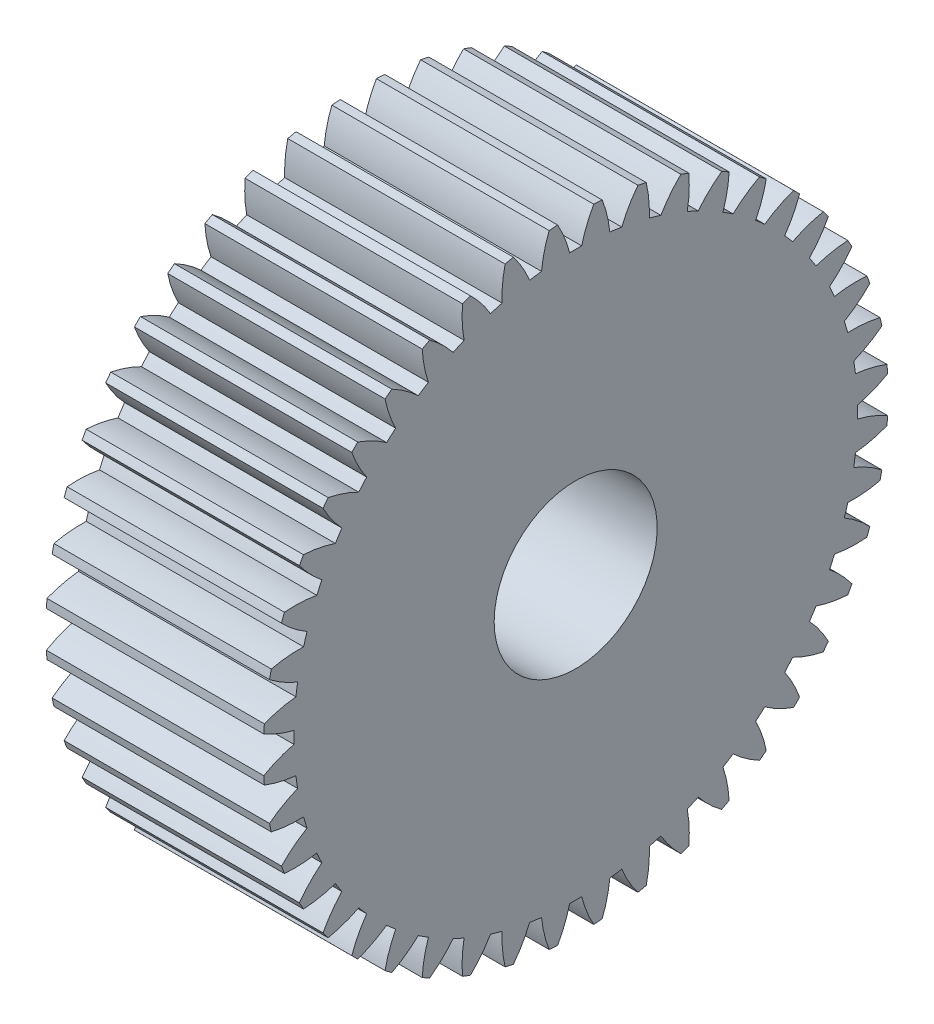
SolidWorks part; units mm, degrees
ref_plane "Plane1" through (0, 0, 0) normal (0, 0, 1) x (1, 0, 0)
ref_plane "Plane2" through (0, 0, 0) normal (0, 1, 0) x (1, 0, 0)
ref_plane "Plane3" through (0, 0, 0) normal (1, 0, 0) x (0, 0, -1)
sketch "HoldingSke" plane through (0, 0, 0) normal (0, 1, 0) x (1, 0, 0)
  line L0 (0, 0) -> (1.4387, -1.3893)
  line L1 (-15, 0) -> (100, 0) construction
  line L2 (0, 0) -> (-2.1039, 2.3779)
  line L3 (0, 0) -> (-11.863, 4.5341)
  line L4 (0, 0) -> (6.2122, 5.9991)
  line L5 (0, 0) -> (-46.8476, -17.4728)
  line L6 (0, 0) -> (-6.6317, -4.4744)
  line L7 (-2.1039, 2.3779) -> (8.6586, 51.2059)
  line L8 (-76.2, 54.61) -> (-75.2, 54.61)
  line L9 (-71.009, 38.7566) -> (-53.1078, 45.2721)
  line L10 (-76.2, 71.12) -> (104.1128, 71.12)
  line L11 (0, 0) -> (-8, 0)
  line L12 (-76.2, 101.6) -> (-76.181, 101.6)
  line L13 (24.9733, 27.94) -> (52.9518, 28.4284)
  line L14 (24.9733, 27.94) -> (24.9743, 27.94)
  line L15 (24.9733, 27.94) -> (100.4006, 29.5858)
  line L16 (-63.627, -0.5) -> (-12.827, -0.5)
  circle A0 centre (0, 0) radius 3
  circle A1 centre (0, 0) radius 10.374
  circle A2 centre (0, 0) radius 37.5
  circle A3 centre (0, 0) radius 3
  dimension "MHD" = 20.748
  dimension "Hub_dia" = 75
  dimension "Bore" = 6
  dimension "MBD" = 6
  dimension "Num_teeth" = 44
  dimension "Pitch" = 2
  dimension "Overall_len" = 50
  dimension "Show_teeth" = 44
  dimension "Thickness" = 8
  dimension "OAL" = 50.0001
  dimension "T_dim" = 1
  dimension "Ap" = 20
  dimension "H" = 19.05
  dimension "Pitch_radius" = 180.3128
  dimension "Width" = 8
  dimension "Backlash" = 0.019
  dimension "Addendum_fac" = 1
  dimension "Dedendum_fac" = 1.25
  dimension "Clearance_fac" = 0.25
  dimension "Dedendum_add" = 0.001
  dimension "Module" = 0.5
sketch "BasProSke" plane through (0, 0, 0) normal (0, 1, 0) x (1, 0, 0)
  line L0 (-10, 0) -> (60, 0) construction
  line L1 (0, 0) -> (0, 11.5)
  line L2 (0, 0) -> (8, 0)
  line L3 (8, 0) -> (8, 11.5)
  line L4 (8, 11.5) -> (0, 11.5)
  dimension "Thickness" = 8
  dimension "Diameter" = 23
revolve "Base-Revolve" add sketch "BasProSke" angle 360 about L0
sketch "TooCutSke" plane through (0, 0, 0) normal (1, 0, 0) x (0, 0, -1)
  line L1 (0, 0) -> (0, 107) construction
  line L2 (0, 0) -> (-0.4259, 10.9918) construction
  line L3 (0, 0) -> (-1.5686, 21.9322) construction
  line L4 (-0.4259, 10.9918) -> (-0.7843, 10.9661) construction
  arc A0 (0.2217, 10.3716) -> (-0.2217, 10.3716) centre (0, 0) ccw
  arc A1 (0.6787, 11.5054) -> (-0.6787, 11.5054) centre (0, 0) ccw
  circle A2 centre (0, 0) radius 11 construction
  circle A3 centre (0, 0) radius 10.3366 construction
  arc A4 (-0.2217, 10.3716) -> (-0.6787, 11.5054) centre (-4.4917, 9.3097) ccw
  arc A5 (0.6787, 11.5054) -> (0.2217, 10.3716) centre (4.4917, 9.3097) ccw
  dimension "Root_dia" = 20.748
  dimension "Overcut_dia" = 23.0508
  dimension "Pitch_dia" = 22
  dimension "Base_dia" = 20.6732
  dimension "Flank_rad" = 4.4
  dimension "Half_ang" = 4.091
  dimension "Half_CT" = 0.3594
extrude "ToothCut" cut sketch "TooCutSke" along normal through all
fillet "Breaks" [suppressed] radius 0.01
fillet "RootFillets" [suppressed] radius 0.126
pattern_circular "TeethCuts" count 44 every 8.182 about axis through (-10, 0, 0) along (1, 0, 0) of "ToothCut", "RootFillets", "Breaks"
sketch "HubNeaOneSke" plane through (0, 0, 0) normal (-1, 0, 0) x (0, 0, 1)
  circle A0 centre (0, 0) radius 10.374
  dimension "Diameter" = 20.748
extrude "HubNearOne" [suppressed] add sketch "HubNeaOneSke" along normal blind 42.0001
sketch "HubNeaBotSke" plane through (0, 0, 0) normal (-1, 0, 0) x (0, 0, 1)
  circle A0 centre (0, 0) radius 10.374
  dimension "Diameter" = 20.748
extrude "HubNearBoth" [suppressed] add sketch "HubNeaBotSke" along normal blind 21
ref_plane "FarPln" through (8, 0, 0) normal (1, 0, 0) x (0, 0, -1)
sketch "HubFarSke" plane through (8, 0, 0) normal (1, 0, 0) x (0, 0, -1)
  circle A0 centre (0, 0) radius 10.374
  dimension "Diameter" = 20.748
extrude "HubFar" [suppressed] add sketch "HubFarSke" along normal blind 21
sketch "BorSke" plane through (0, 0, 0) normal (1, 0, 0) x (0, 0, -1)
  circle A0 centre (0, 0) radius 3
  dimension "Diameter" = 6
extrude "Bore" cut sketch "BorSke" along normal mid plane 100.0001
sketch "KeySke" plane through (0, 0, 0) normal (1, 0, 0) x (0, 0, -1)
  line L0 (-1, 0) -> (-1, 4)
  line L1 (-1, 4) -> (1, 4)
  line L2 (1, 4) -> (1, 0)
  line L3 (0, 0) -> (0, 34) construction
  line L4 (-1, 0) -> (1, 0)
  dimension "Offset" = 4
  dimension "Width" = 2
extrude "Keyway" [suppressed] cut sketch "KeySke" along normal mid plane 100.0001
pattern_circular "Keyway2" [suppressed] count 2 every 90 about axis through (-10, 0, 0) along (1, 0, 0)
equation "' \"Module@HoldingSke\" = 6.35"
equation "' \"Num_teeth@HoldingSke\" = 12"
equation "' \"Ap@HoldingSke\" =  20"
equation "' \"Ap@HoldingSke\" = 20"
equation "' \"Width@HoldingSke\" = 0.5 * 25.4"
equation "' \"Hub_dia@HoldingSke\"= 1 * 25.4"
equation "' \"Hub_dia@HoldingSke\" = 1 * 25.4"
equation "' \"Overall_len@HoldingSke\" = 1.0 * 25.4"
equation "' \"Bore@HoldingSke\" = 0.75 * 25.4"
equation "' \"T_dim@HoldingSke\" = 0.1 * 25.4"
equation "' \"Width@KeySke\" = 0.25 * 25.4"
equation "' \"Show_teeth@HoldingSke\" = 13"
equation "' \"Backlash@HoldingSke\" = 0.009 * 25.4"
equation "' \"Addendum_fac@HoldingSke\" = 1.0"
equation "' \"Dedendum_fac@HoldingSke\" = 1.25"
equation "' \"Dedendum_add@HoldingSke\" = 0.00005 * 25.4"
equation "' \"Clearance_fac@HoldingSke\" = 0.25"
equation "\"Pitch@HoldingSke\" = 1 / \"Module@HoldingSke\""
equation "\"Overcut_dia@TooCutSke\" = (\"Num_teeth@HoldingSke\" + 2 * \"Addendum_fac@HoldingSke\") / \"Pitch@HoldingSke\" + 0.002 * 25.4"
equation "\"Pitch_dia@TooCutSke\" = \"Num_teeth@HoldingSke\" / \"Pitch@HoldingSke\""
equation "\"Base_dia@TooCutSke\" = \"Num_teeth@HoldingSke\" / \"Pitch@HoldingSke\" * cos((\"Ap@HoldingSke\"  * 3.14159265 / 180))"
equation "\"Root_dia@TooCutSke\" = (\"Num_teeth@HoldingSke\" + 2) / \"Pitch@HoldingSke\" - 2 * (\"Addendum_fac@HoldingSke\" + \"Dedendum_fac@HoldingSke\") / \"Pitch@HoldingSke\" - \"Dedendum_add@HoldingSke\" * 2"
equation "\"Half_ang@TooCutSke\" = 180 / \"Num_teeth@HoldingSke\""
equation "\"Half_CT@TooCutSke\" = \"Num_teeth@HoldingSke\" / \"Pitch@HoldingSke\" * sin((3.14159265 / 2 / \"Num_teeth@HoldingSke\")) / 2 - 7 * \"Backlash@HoldingSke\" / 4"
equation "\"Flank_rad@TooCutSke\" = \"Num_teeth@HoldingSke\" / \"Pitch@HoldingSke\" / 5"
equation "\"Radius@RootFillets\" = \"Clearance_fac@HoldingSke\" / \"Pitch@HoldingSke\" + \"Dedendum_add@HoldingSke\""
equation "\"Break_rad@Breaks\" = 0.02 / \"Pitch@HoldingSke\""
equation "\"Thickness@HoldingSke\" = \"Width@HoldingSke\""
equation "\"OAL@HoldingSke\" = \"Thickness@HoldingSke\""
equation "\"MHD@HoldingSke\" = (\"Num_teeth@HoldingSke\" + 2) / \"Pitch@HoldingSke\" - 2 * (\"Addendum_fac@HoldingSke\" + \"Dedendum_fac@HoldingSke\")  / \"Pitch@HoldingSke\" - \"Dedendum_add@HoldingSke\" * 2"
equation "\"MBD@HoldingSke\" = (\"Num_teeth@HoldingSke\" + 2) / \"Pitch@HoldingSke\" - 2 * (\"Addendum_fac@HoldingSke\" + \"Dedendum_fac@HoldingSke\")  / \"Pitch@HoldingSke\" - \"Dedendum_add@HoldingSke\" * 2 - 0.002 * 25.4"
equation "\"MHD@HoldingSke\" = ((sgn( \"MHD@HoldingSke\" - \"Hub_dia@HoldingSke\" )-1)*( \"MHD@HoldingSke\" - \"Hub_dia@HoldingSke\" ))/-2+ \"Hub_dia@HoldingSke\""
equation "\"MBD@HoldingSke\" = ((sgn( \"MBD@HoldingSke\" - \"Bore@HoldingSke\" )-1)*( \"MBD@HoldingSke\" - \"Bore@HoldingSke\" ))/-2+ \"Bore@HoldingSke\""
equation "\"OAL@HoldingSke\" = ((sgn( \"OAL@HoldingSke\" - \"Overall_len@HoldingSke\" )+1)*( \"OAL@HoldingSke\" - \"Overall_len@HoldingSke\" ))/2 + \"Overall_len@HoldingSke\" + 0.000002 * 25.4"
equation "\"Num_teeth@TeethCuts\" = int( \"Show_teeth@HoldingSke\" ) + 1"
equation "\"Num_teeth@TeethCuts\" = ((sgn( \"Num_teeth@TeethCuts\" - \"Num_teeth@HoldingSke\" )-1)*( \"Num_teeth@TeethCuts\" - \"Num_teeth@HoldingSke\" ))/-2+ \"Num_teeth@HoldingSke\""
equation "\"Num_teeth@TeethCuts\" = ((sgn( \"Num_teeth@TeethCuts\" - 2.0)+1)*( \"Num_teeth@TeethCuts\" - 2.0))/2 +2.0"
equation "\"Angle@TeethCuts\" = 360.0 / \"Num_teeth@HoldingSke\""
equation "\"Diameter@BasProSke\" = (\"Num_teeth@HoldingSke\" + 2 * \"Addendum_fac@HoldingSke\") / \"Pitch@HoldingSke\""
equation "\"Thickness@BasProSke\"  = \"Thickness@HoldingSke\""
equation "' \"Fillet_rad@BasProSke\" =  \"Thickness@HoldingSke\" * 0.05"
equation "' \"Fillet_rad@BasProSke\" = \"Thickness@HoldingSke\" * 0.05"
equation "\"MHD@HoldingSke\" = ((sgn( \"MHD@HoldingSke\" - \"Root_dia@TooCutSke\" )-1)*( \"MHD@HoldingSke\" - \"Root_dia@TooCutSke\" ))/-2+ \"Root_dia@TooCutSke\""
equation "\"Diameter@HubNeaOneSke\" = \"MHD@HoldingSke\""
equation "\"Length@HubNearOne\" = \"OAL@HoldingSke\" - \"Thickness@BasProSke\""
equation "\"Diameter@HubNeaBotSke\" = \"MHD@HoldingSke\""
equation "\"Length@HubNearBoth\" = ( \"OAL@HoldingSke\" - \"Thickness@BasProSke\" ) / 2.0"
equation "\"Thickness@FarPln\" = \"Thickness@BasProSke\""
equation "\"Diameter@HubFarSke\" = \"MHD@HoldingSke\""
equation "\"Length@HubFar\" = ( \"OAL@HoldingSke\" - \"Thickness@BasProSke\" ) / 2.0"
equation "\"Diameter@BorSke\" = \"MBD@HoldingSke\""
equation "\"D1@Bore\" = \"OAL@HoldingSke\" * 2.0"
equation "\"D1@Keyway\" = \"OAL@HoldingSke\" * 2.0"
equation "\"Offset@KeySke\" = \"T_dim@HoldingSke\" + \"MBD@HoldingSke\" / 2.0"
